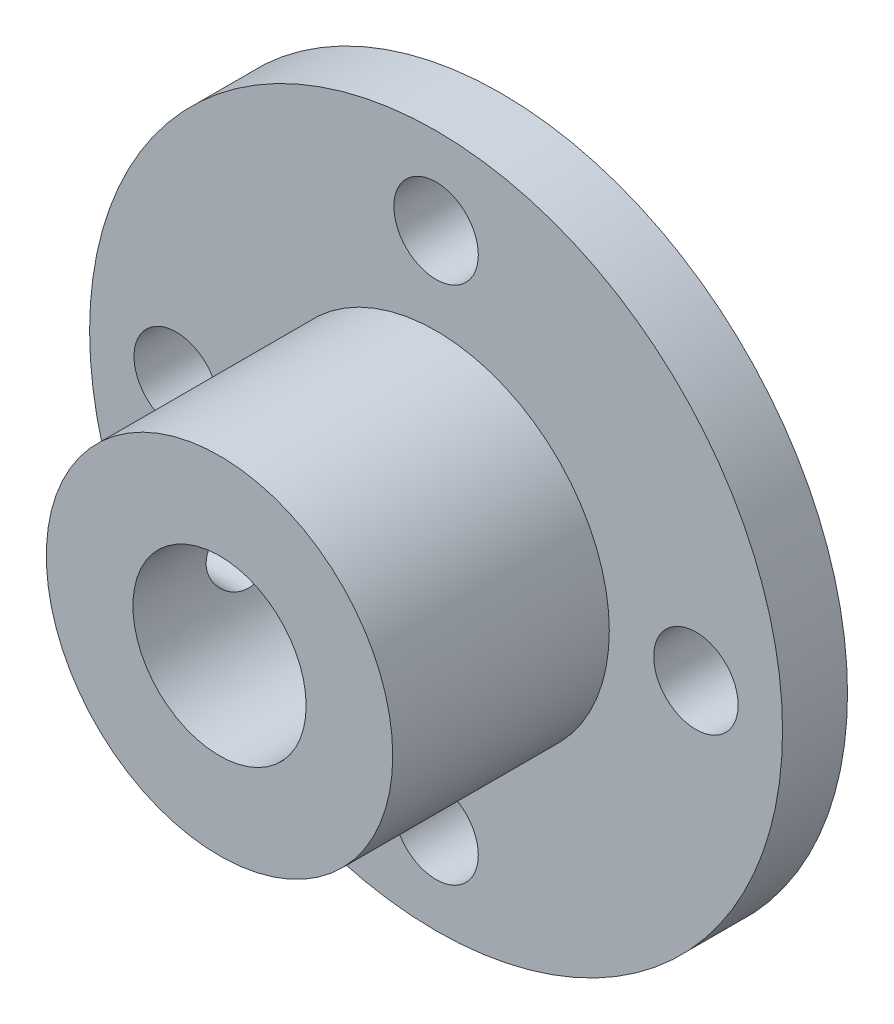
SolidWorks part; units mm, degrees
ref_plane "Piano frontale" through (0, 0, 0) normal (0, 0, 1) x (1, 0, 0)
ref_plane "Piano superiore" through (0, 0, 0) normal (0, 1, 0) x (1, 0, 0)
ref_plane "Piano destro" through (0, 0, 0) normal (1, 0, 0) x (0, 0, -1)
sketch "Schizzo1" plane through (0, 0, 0) normal (0, 1, 0) x (1, 0, 0)
  line L0 (16, 0) -> (0, 0)
  line L1 (0, 0) -> (0, -3)
  line L2 (0, -3) -> (16, -3)
  line L3 (16, -3) -> (16, 0)
  line L4 (0, 0) -> (0, -3) construction
  dimension "D1" = 16
  dimension "D2" = 3
revolve "Rivoluzione1" add sketch "Schizzo1" angle 360 about L4
sketch "Schizzo2" plane through (0, 0, 3) normal (0, 0, 1) x (1, 0, 0)
  circle A0 centre (0, 0) radius 8
  dimension "D1" = 16
extrude "Estrusione-Estrusione1" add sketch "Schizzo2" along normal blind 10
hole_wizard "Foro Ø3.9 (3.9)-1" positions "Schizzo4" profile "Schizzo3" hole size "Ø3.9" standard "Ansi Metric"
sketch "Schizzo4" plane through (0, 0, 3) normal (0, 0, 1) x (1, 0, 0)
  point P0 (12, 0)
  point P1 (0, 12)
  point P2 (-12, 0)
  point P3 (0, -12)
sketch "Schizzo3" plane through (12, 0, 3) normal (1, 0, 0) x (0, -1, 0)
  line L0 (0, 0) -> (0, 3)
  line L1 (0, 3) -> (1.95, 3)
  line L2 (1.95, 3) -> (1.95, 0)
  line L5 (1.95, 0) -> (0, 0)
  line L11 (0, -6.35) -> (0, 107.95) construction
  dimension "Thru Hole Dia." = 3.9
  dimension "Thru Hole Depth" = 3
hole_wizard "Foro Ø8.0 (8)-1" positions "Schizzo6" profile "Schizzo5" hole size "Ø8.0" standard "Ansi Metric"
sketch "Schizzo6" plane through (0, 0, 13) normal (0, 0, 1) x (1, 0, 0)
  point P0 (0, 0)
sketch "Schizzo5" plane through (0, 0, 13) normal (1, 0, 0) x (0, -1, 0)
  line L0 (0, 0) -> (0, 13)
  line L1 (0, 13) -> (4, 13)
  line L2 (4, 13) -> (4, 0)
  line L5 (4, 0) -> (0, 0)
  line L11 (0, -6.35) -> (0, 107.95) construction
  dimension "Thru Hole Dia." = 8
  dimension "Thru Hole Depth" = 13
hole_wizard "Foro per Vite M3-1" positions "Schizzo3D1" profile "Schizzo7" hole size "M3" standard "Ansi Metric"
sketch3d "Schizzo3D1"
  point P0 (-8, 0, 8)
sketch "Schizzo7" plane through (-8, 0, 8) normal (0, 1, 0) x (0, 0, 1)
  line L0 (0, 0) -> (0, 4)
  line L1 (0, 4) -> (1.62, 4)
  line L2 (1.62, 4) -> (1.62, 0)
  line L5 (1.62, 0) -> (0, 0)
  line L11 (0, -6.35) -> (0, 107.95) construction
  dimension "Thru Hole Dia." = 3.24
  dimension "Thru Hole Depth" = 4
